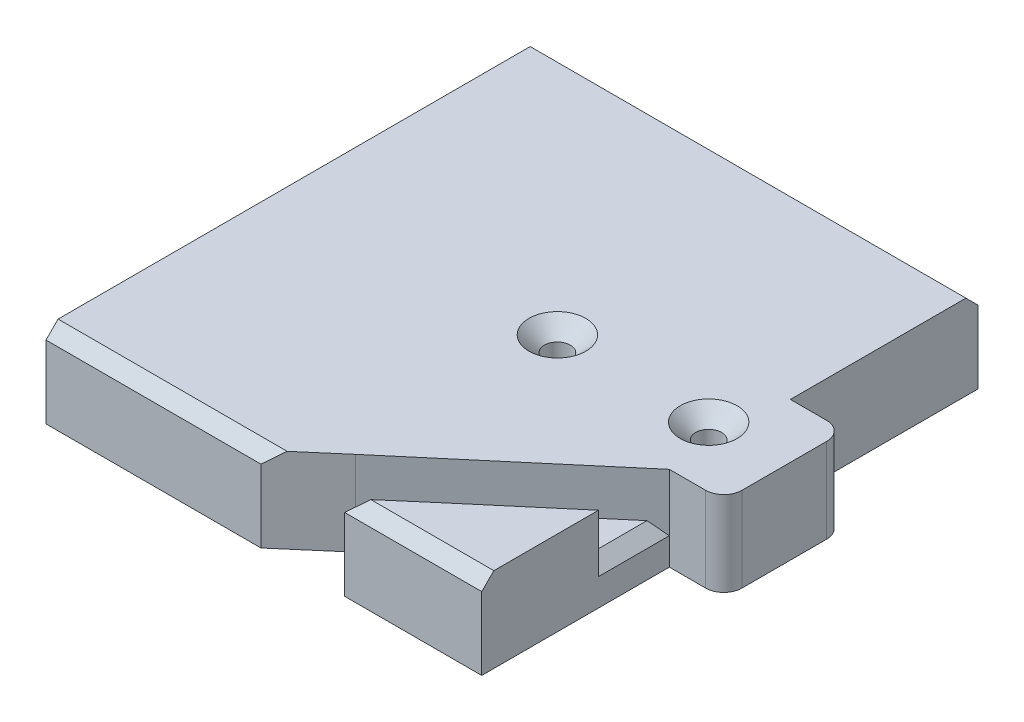
SolidWorks part; units mm, degrees
ref_plane "Plan de face" through (0, 0, 0) normal (0, 0, 1) x (1, 0, 0)
ref_plane "Plan de dessus" through (0, 0, 0) normal (0, 1, 0) x (1, 0, 0)
ref_plane "Plan de droite" through (0, 0, 0) normal (1, 0, 0) x (0, 0, -1)
sketch "Esquisse2" plane through (0, 0, 0) normal (0, 0, 1) x (1, 0, 0)
  line L1 (-36, -7) -> (36, -7)
  line L2 (-36, -7) -> (-36, 7)
  line L3 (-36, 7) -> (36, 7)
  line L4 (36, -7) -> (36, 7)
  line L5 (-36, -7) -> (36, 7) construction
  line L6 (-36, 7) -> (36, -7) construction
  point P0 (0, 0)
  dimension "D1" = 14
  dimension "D2" = 72
extrude "Boss.-Extru.1" add sketch "Esquisse2" along normal mid plane 82 contours L3 L4 L1 L2
sketch "Esquisse12" plane through (0, 7, 0) normal (0, 1, 0) x (1, 0, 0)
  line L0 (0, 0) -> (53.9301, 0) construction
  line L1 (45, 10) -> (45, -10)
  line L2 (45, -10) -> (36, -10)
  line L3 (36, -41) -> (36, 41) construction
  line L4 (36, -10) -> (36, 10)
  line L5 (45, 10) -> (36, 10)
  point P10 (36, 0)
  point P11 (45, 0)
  dimension "D1" = 20
  dimension "D2" = 9
extrude "Boss.-Extru.6" add sketch "Esquisse12" against normal up to surface (14 mm away) up to face at (0, -7, 0)
hole_wizard "Fraisage pour vis à tête fraisée M41" positions "Esquisse15" profile "Esquisse14" countersink size "M4" standard "Ansi Metric" end condition through all
sketch "Esquisse15" plane through (0, 7, 0) normal (0, 1, 0) x (1, 0, 0)
  line L0 (45, -10) -> (45, 10) construction
  point P0 (32.5, 0)
  point P2 (7.5, 0)
  point P8 (45, 0)
sketch "Esquisse14" plane through (32.5, 7, 0) normal (1, 0, 0) x (0, 0, 1)
  line L0 (0, 0) -> (0, 14)
  line L1 (0, 14) -> (2.15, 14)
  line L2 (2.15, 14) -> (2.15, 2.55)
  line L3 (2.15, 2.55) -> (4.7, 0)
  line L5 (4.7, 0) -> (0, 0)
  line L6 (-2.15, 2.55) -> (-4.7, 0) construction
  line L11 (0, -6.35) -> (0, 107.95) construction
  dimension "Diamètre du perçage jusqu'au prochain" = 4.3
  dimension "Profondeur du perçage jusqu'au prochain" = 14
  dimension "Diamètre du fraisage entrant" = 9.4
  dimension "Angle du fraisage entrant" = 90
sketch "Esquisse6" plane through (0, 0, 41) normal (0, 0, 1) x (1, 0, 0)
  line L0 (-36, -7) -> (36, -7) construction
  line L1 (-28, -7) -> (-8, -7)
  line L2 (-28, -7) -> (-28, 3)
  line L3 (-28, 3) -> (-8, 3)
  line L4 (-8, -7) -> (-8, 3)
  line L8 (-36, -7) -> (-36, 7) construction
  line L9 (-36, 7) -> (36, 7) construction
  dimension "D1" = 8
  dimension "D2" = 20
  dimension "D3" = 4
extrude "Enlèv. mat.-Extru.3" cut sketch "Esquisse6" against normal up to next
sketch "Esquisse5" plane through (0, -7, 0) normal (0, 1, 0) x (1, 0, 0)
  line L0 (-36, -41) -> (-36, 41) construction
  line L1 (-36, 25) -> (-30.5, 25)
  line L2 (-36, 25) -> (-36, -25)
  line L3 (-36, -25) -> (-30.5, -25)
  line L4 (-30.5, 25) -> (-30.5, -25)
  point P6 (-30.5, 0)
  dimension "D1" = 5.5
  dimension "D2" = 50
extrude "Enlèv. mat.-Extru.2" cut sketch "Esquisse5" along normal blind 7
chamfer "Chanfrein1" distance 2 angle 45 2 edges at (0, 7, -41) (0, 7, 41)
sketch "Esquisse16" plane through (0, 3, 0) normal (0, -1, 0) x (1, 0, 0)
  line L0 (-28, -41) -> (-8, -41)
  line L1 (-28, -41) -> (-28, -34)
  line L2 (-8, -41) -> (-8, -34)
  line L3 (-28, -34) -> (-8, -34)
  dimension "D1" = 7
extrude "Boss.-Extru.7" add sketch "Esquisse16" along normal up to surface (10 mm away) up to face at (32.5, -7, 2.15)
mirror "Symétrie1" about plane through (0, 0, 0) normal (0, 0, 1) of "Boss.-Extru.7"
sketch "Esquisse17" plane through (0, 7, 0) normal (0, 1, 0) x (1, 0, 0)
  line L0 (13.342, -41) -> (36, -21.5723) construction
  line L1 (35.6698, -10) -> (-0.4846, -41) construction
  line L2 (13.342, -41) -> (21.7392, -33.8)
  line L3 (7.9126, -33.8) -> (-0.4846, -41)
  line L4 (7.9126, -33.8) -> (21.7392, -33.8)
  line L5 (-0.4846, -41) -> (13.342, -41)
  line L6 (21.7392, -33.8) -> (7.9126, -33.8) construction
extrude "Enlèv. mat.-Extru.4" cut sketch "Esquisse17" against normal up to vertex
sketch "Esquisse18" plane through (0, 7, 0) normal (0, 1, 0) x (1, 0, 0)
  line L0 (7.9126, -33.8) -> (36, -10)
  line L1 (36, -21.716) -> (21.7392, -33.8)
  line L2 (36, -39) -> (36, -10) construction
  line L3 (36, -10) -> (36, -21.716)
  line L4 (7.9126, -33.8) -> (21.7392, -33.8)
extrude "Enlèv. mat.-Extru.5" cut sketch "Esquisse18" against normal blind 7.5
chamfer "Chanfrein2" distance 2 angle 45 2 edges at (36, -0.5, 15.858) (14.8259, -0.5, 33.8)
fillet "Congé3" radius 3 2 edges at (45, 0, -10) (45, 0, 10)
